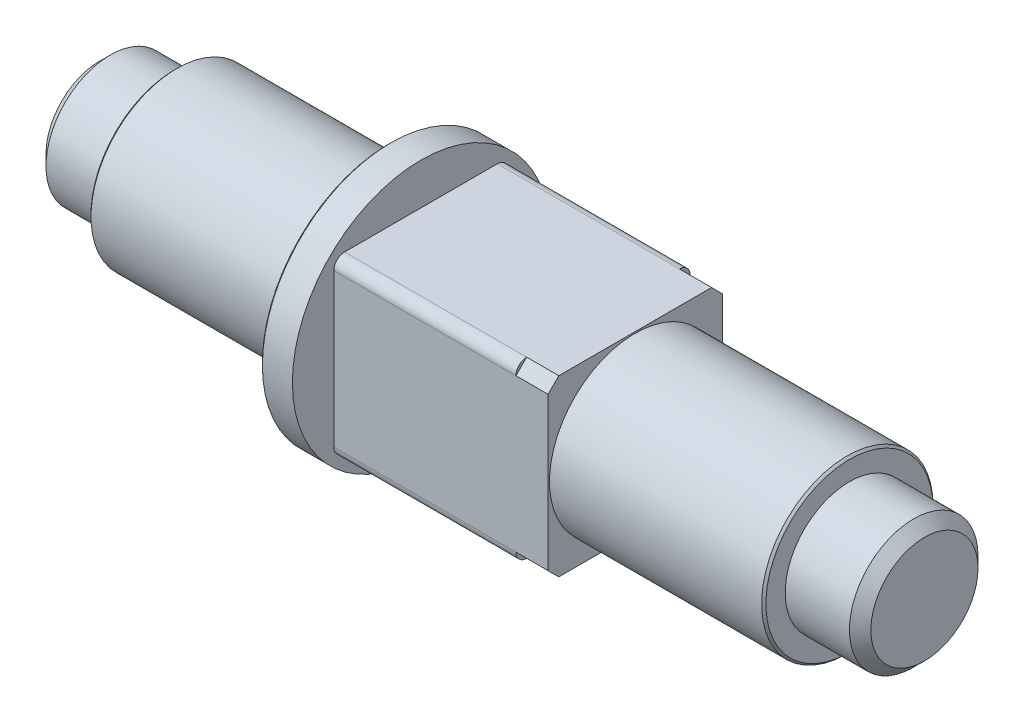
SolidWorks part; units mm, degrees
ref_plane "前视基准面" through (0, 0, 0) normal (0, 0, 1) x (1, 0, 0)
ref_plane "上视基准面" through (0, 0, 0) normal (0, 1, 0) x (1, 0, 0)
ref_plane "右视基准面" through (0, 0, 0) normal (1, 0, 0) x (0, 0, -1)
sketch "草图1" plane through (0, 0, 0) normal (0, 0, 1) x (1, 0, 0)
  line L0 (0, 0) -> (0, 2.5)
  line L1 (0.5, 3) -> (3.5, 3)
  line L2 (3.5, 3) -> (3.5, 3.9)
  line L3 (3.6, 4) -> (13.5, 4)
  line L4 (13.5, 4) -> (13.5, 5.9)
  line L5 (13.6, 6) -> (15, 6)
  line L6 (15, 6) -> (15, 0)
  line L7 (15, 0) -> (0, 0)
  line L8 (3.5, 3.9) -> (3.6, 4)
  line L9 (13.5, 5.9) -> (13.6, 6)
  line L10 (0, 2.5) -> (0.5, 3)
  point P1 (0, 3)
  point P5 (3.5, 4)
  point P7 (13.5, 6)
revolve "旋转1" add sketch "草图1" angle 360 about L7
ref_plane "基准面1" through (15, 0, 0) normal (1, 0, 0) x (0, 0, -1)
sketch "草图2" plane through (15, 0, 0) normal (1, 0, 0) x (0, 0, -1)
  line L1 (-3.5659, 4.0659) -> (3.5659, 4.0659)
  line L2 (-4.0659, 3.5659) -> (-4.0659, -3.5659)
  line L3 (-3.5659, -4.0659) -> (3.5659, -4.0659)
  line L4 (4.0659, 3.5659) -> (4.0659, -3.5659)
  line L5 (-4.0659, 4.0659) -> (4.0659, -4.0659) construction
  line L6 (-4.0659, -4.0659) -> (4.0659, 4.0659) construction
  arc A0 (-4.0659, -3.5659) -> (-3.5659, -4.0659) centre (-3.5659, -3.5659) ccw
  arc A1 (3.5659, -4.0659) -> (4.0659, -3.5659) centre (3.5659, -3.5659) ccw
  arc A2 (4.0659, 3.5659) -> (3.5659, 4.0659) centre (3.5659, 3.5659) ccw
  arc A3 (-4.0659, 3.5659) -> (-3.5659, 4.0659) centre (-3.5659, 3.5659) cw
  point P0 (0, 0)
  point P5 (0, 0)
  point P289 (3, -3)
  dimension "D1" = 0.5
extrude "凸台-拉伸1" add sketch "草图2" along normal blind 10
ref_plane "基准面2" through (25, 0, 0) normal (1, 0, 0) x (0, 0, -1)
sketch "草图3" plane through (25, 0, 0) normal (1, 0, 0) x (0, 0, -1)
  line L0 (-4.0659, 3.5659) -> (-3.5659, 4.0659)
  line L5 (-4.0659, 4.0659) -> (4.0659, -4.0659) construction
  line L6 (-4.0659, -4.0659) -> (4.0659, 4.0659) construction
  line L7 (3.5659, 4.0659) -> (4.0659, 3.5659)
  line L8 (-4.0659, -3.5659) -> (-3.5659, -4.0659)
  line L9 (3.5659, -4.0659) -> (4.0659, -3.5659)
  line L10 (-3.5659, 4.0659) -> (-4.0659, 4.0659)
  line L11 (-4.0659, 4.0659) -> (-4.0659, 3.5659)
  line L12 (3.5659, 4.0659) -> (4.0659, 4.0659)
  line L13 (4.0659, 4.0659) -> (4.0659, 3.5659)
  line L14 (4.0659, -3.5659) -> (4.0659, -4.0659)
  line L15 (4.0659, -4.0659) -> (3.5659, -4.0659)
  line L16 (-4.0659, -3.5659) -> (-4.0659, -4.0659)
  line L17 (-4.0659, -4.0659) -> (-3.5659, -4.0659)
  point P0 (0, 0)
extrude "切除-拉伸2" cut sketch "草图3" against normal blind 1.5
sketch "草图5" plane through (0, 0, 0) normal (0, 0, 1) x (1, 0, 0)
  line L0 (35, 3.9) -> (35, 3)
  line L1 (25, 4) -> (34.9, 4)
  line L2 (25, -6.6) -> (25, 6.6) construction
  line L3 (38.5, 0) -> (25, 0)
  line L4 (25, 0) -> (25, 4)
  line L5 (38.5, 2.5) -> (38.5, 0)
  line L6 (35, 3) -> (38, 3)
  line L7 (38, 3) -> (38.5, 2.5)
  line L8 (34.9, 4) -> (35, 3.9)
  point P4 (35, 4)
  point P13 (38.5, 3)
revolve "旋转2" add sketch "草图5" angle 360 about L3
